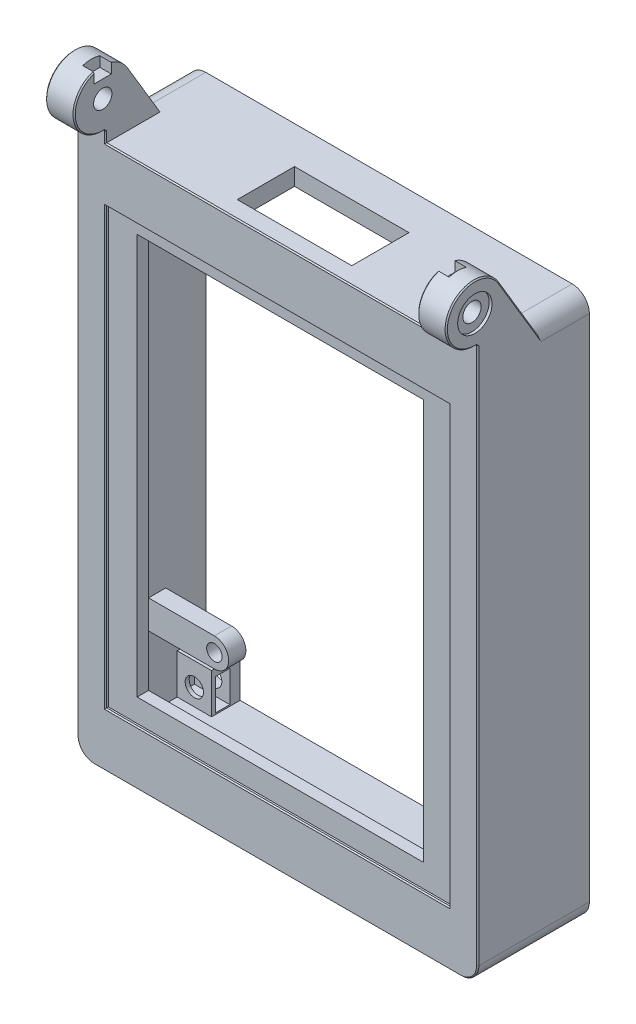
SolidWorks part; units mm, degrees
ref_plane "前视基准面" through (0, 0, 0) normal (0, 0, 1) x (1, 0, 0)
ref_plane "上视基准面" through (0, 0, 0) normal (0, 1, 0) x (1, 0, 0)
ref_plane "右视基准面" through (0, 0, 0) normal (1, 0, 0) x (0, 0, -1)
other "Configuration Table"
sketch "草图1" plane through (0, 0, 0) normal (0, 0, 1) x (1, 0, 0)
  line L1 (-35, -47.5) -> (35, -47.5)
  line L2 (-35, -47.5) -> (-35, 47.5)
  line L3 (-35, 47.5) -> (35, 47.5)
  line L4 (35, -47.5) -> (35, 47.5)
  line L5 (-35, -47.5) -> (35, 47.5) construction
  line L6 (-35, 47.5) -> (35, -47.5) construction
  point P0 (0, 0)
  dimension "D1" = 70
  dimension "D2" = 95
extrude "凸台-拉伸1" add sketch "草图1" along normal blind 20
shell "抽壳1" thickness 3
sketch "草图2" plane through (0, 0, 20) normal (0, 0, 1) x (1, 0, 0)
  line L1 (-30, -38) -> (30, -38)
  line L2 (-30, -38) -> (-30, 38)
  line L3 (-30, 38) -> (30, 38)
  line L4 (30, -38) -> (30, 38)
  line L5 (-30, -38) -> (30, 38) construction
  line L6 (-30, 38) -> (30, -38) construction
  point P0 (0, 0)
  dimension "D1" = 60
  dimension "D2" = 76
extrude "切除-拉伸1" cut sketch "草图2" against normal blind 1
sketch "草图3" plane through (0, 0, 19) normal (0, 0, 1) x (1, 0, 0)
  line L0 (30, 38) -> (-30, 38) construction
  line L5 (-25, 36) -> (25, 36)
  line L6 (-25, 36) -> (-25, -34)
  line L7 (-25, -34) -> (25, -34)
  line L8 (25, 36) -> (25, -34)
  dimension "D1" = 2
  dimension "D2" = 50
  dimension "D3" = 25
  dimension "D4" = 70
extrude "切除-拉伸2" cut sketch "草图3" against normal blind 20
ref_plane "基准面1" through (0, 0, 10) normal (0, 0, 1) x (1, 0, 0)
sketch "草图4" plane through (0, 0, 10) normal (0, 0, 1) x (1, 0, 0)
  line L13 (20.5, 33) -> (32, 33)
  line L14 (32, -44.5) -> (32, 44.5) construction
  line L15 (32, 33) -> (32, 28)
  line L16 (32, -44.5) -> (32, 44.5) construction
  line L21 (-20.5, -29.5) -> (20.5, -29.5) construction
  line L22 (-20.5, 30.5) -> (-20.5, -29.5) construction
  line L23 (20.5, 30.5) -> (-20.5, 30.5) construction
  line L24 (20.5, -29.5) -> (20.5, 30.5) construction
  line L25 (32, 28) -> (20.5, 28)
  line L26 (-20.5, 33) -> (-32, 33)
  line L29 (-32, 33) -> (-32, 28)
  line L30 (-32, 44.5) -> (-32, -44.5) construction
  line L31 (-32, 28) -> (-20.5, 28)
  line L32 (-20.5, -27) -> (-32, -27)
  line L33 (-32, 44.5) -> (-32, -44.5) construction
  line L34 (-32, -27) -> (-32, -32)
  line L35 (-32, -32) -> (-20.5, -32)
  line L36 (20.5, -27) -> (32, -27)
  line L37 (32, -27) -> (32, -32)
  line L38 (32, -32) -> (20.5, -32)
  circle A0 centre (-20.5, 30.5) radius 1.35
  circle A1 centre (20.5, 30.5) radius 1.35
  circle A2 centre (-20.5, -29.5) radius 1.35
  circle A3 centre (20.5, -29.5) radius 1.35
  arc A4 (-20.5, 28) -> (-20.5, 33) centre (-20.5, 30.5) ccw
  arc A5 (20.5, 33) -> (20.5, 28) centre (20.5, 30.5) ccw
  arc A6 (-20.5, -32) -> (-20.5, -27) centre (-20.5, -29.5) ccw
  arc A7 (20.5, -27) -> (20.5, -32) centre (20.5, -29.5) ccw
  dimension "D2" = 2.7
  dimension "D3" = 2.7
  dimension "D4" = 2.7
  dimension "D5" = 2.7
  dimension "D6" = 5
  dimension "D7" = 5
  dimension "D8" = 5
  dimension "D9" = 5
  dimension "D10" = 20.5
  dimension "D1" = 60
extrude "凸台-拉伸2" add sketch "草图4" against normal blind 3
sketch "草图5" plane through (-32, 0, 0) normal (1, 0, 0) x (0, 0, -1)
  line L0 (0, 44.5) -> (0, 37.5)
  line L1 (0, 44.5) -> (0, -44.5) construction
  line L2 (0, 37.5) -> (-5, 37.5)
  line L3 (-5, 37.5) -> (-5, 44.5)
  line L4 (-17, 44.5) -> (0, 44.5) construction
  line L5 (-5, 44.5) -> (0, 44.5)
  line L6 (4.8105, 41.5) -> (-10.1752, 41.5) construction
  line L7 (-20, 47.5) -> (0, 47.5) construction
  dimension "D1" = 5
  dimension "D2" = 6
  dimension "D3" = 7
extrude "凸台-拉伸3" add sketch "草图5" along normal blind 6
sketch "草图6" plane through (-26, 0, 0) normal (1, 0, 0) x (0, 0, -1)
  line L0 (-8.1923, 41.5) -> (5.3609, 41.5) construction
  line L1 (-20, 47.5) -> (0, 47.5) construction
  line L2 (0, 37.5) -> (0, 44.5) construction
  line L3 (-4.3, 44.25) -> (-1.8, 44.25)
  line L4 (-4.3, 44.25) -> (-4.3, 38.75)
  line L5 (-4.3, 38.75) -> (-1.8, 38.75)
  line L6 (-1.8, 44.25) -> (-1.8, 38.75)
  dimension "D1" = 6
  dimension "D2" = 2.5
  dimension "D3" = 2.75
  dimension "D4" = 2.75
  dimension "D5" = 1.8
extrude "切除-拉伸3" cut sketch "草图6" against normal blind 6.2
sketch "草图7" plane through (0, 0, 0) normal (0, 0, -1) x (-1, 0, 0)
  line L0 (-35, 47.5) -> (35, 47.5) construction
  line L1 (35, 47.5) -> (35, -47.5) construction
  circle A0 centre (29, 41.5) radius 1.6
  dimension "D3" = 3.2
  dimension "D1" = 6
  dimension "D2" = 6
extrude "切除-拉伸4" cut sketch "草图7" against normal blind 6.2
mirror "镜向1" about plane through (0, 0, 0) normal (0, 1, 0) of "凸台-拉伸3"
mirror "镜向2" about plane through (0, 0, 0) normal (1, 0, 0) of "镜向1", "凸台-拉伸3"
mirror "镜向3" about plane through (0, 0, 0) normal (0, 1, 0) of "切除-拉伸3"
mirror "镜向4" about plane through (0, 0, 0) normal (1, 0, 0) of "镜向3", "切除-拉伸3"
mirror "镜向5" about plane through (0, 0, 0) normal (0, 1, 0) of "切除-拉伸4"
mirror "镜向6" about plane through (0, 0, 0) normal (1, 0, 0) of "镜向5", "切除-拉伸4"
sketch "草图8" plane through (35, 0, 0) normal (1, 0, 0) x (0, 0, -1)
  line L0 (0, 47.5) -> (0, 49.5) construction
  line L1 (-20, 47.5) -> (0, 47.5) construction
  line L2 (0, -47.5) -> (0, 47.5) construction
  line L3 (-4.2936, 57.0623) -> (-10, 47.5) construction
  line L4 (-20, 47.5) -> (0, 47.5) construction
  line L5 (-10, 47.5) -> (-10, 58.6086) construction
  line L6 (-15.7064, 57.0623) -> (-10, 47.5)
  line L7 (-20, 47.5) -> (-20, 49.5)
  line L8 (-10, 47.5) -> (-20, 47.5)
  arc A0 (0, 49.5) -> (-4.2936, 57.0623) centre (0, 54.5) ccw construction
  arc A1 (-20, 49.5) -> (-15.7064, 57.0623) centre (-20, 54.5) cw
  dimension "D1" = 10
  dimension "D2" = 7
  dimension "D3" = 10
  dimension "D4" = 7
extrude "凸台-拉伸4" add sketch "草图8" against normal up to surface (70 mm away) up to face at (-35, 0, 10)
sketch "草图9" plane through (35, 0, 0) normal (1, 0, 0) x (0, 0, -1)
  circle A0 centre (-20, 54.5) radius 1.6
  dimension "D1" = 3.2
extrude "切除-拉伸5" cut sketch "草图9" against normal up to surface (70 mm away) up to face at (-35, 18.375, 12.0335)
sketch "草图10" plane through (0, 0, 0) normal (0, 0, -1) x (-1, 0, 0)
  line L0 (35, 59.5) -> (-35, 59.5) construction
  line L1 (-30, 59.5) -> (30, 59.5)
  line L2 (-30, 59.5) -> (-30, 47.5)
  line L3 (-30, 47.5) -> (30, 47.5)
  line L4 (30, 59.5) -> (30, 47.5)
  line L5 (35, 47.5) -> (-35, 47.5) construction
  line L6 (35, 57.0623) -> (35, 47.5) construction
  line L7 (-35, 47.5) -> (-35, 57.0623) construction
  dimension "D1" = 5
  dimension "D2" = 5
extrude "切除-拉伸6" cut sketch "草图10" against normal blind 30
sketch "草图11" plane through (-30, 0, 0) normal (1, 0, 0) x (0, 0, -1)
  line L0 (-20, 54.5) -> (-20, 62.1842) construction
  line L1 (-21.5, 64.5) -> (-18.5, 64.5)
  line L2 (-21.5, 64.5) -> (-21.5, 57.5)
  line L3 (-21.5, 57.5) -> (-18.5, 57.5)
  line L4 (-18.5, 64.5) -> (-18.5, 57.5)
  dimension "D1" = 1.5
  dimension "D2" = 1.5
  dimension "D3" = 3
  dimension "D4" = 10
extrude "切除-拉伸7" cut sketch "草图11" against normal blind 2
mirror "镜向7" about plane through (0, 0, 0) normal (1, 0, 0) of "切除-拉伸7"
sketch "草图12" plane through (35, 0, 0) normal (1, 0, 0) x (0, 0, -1)
  circle A0 centre (-20, 54.5) radius 3
  dimension "D1" = 6
extrude "切除-拉伸8" cut sketch "草图12" against normal blind 0.5
mirror "镜向8" about plane through (0, 0, 0) normal (1, 0, 0) of "切除-拉伸8"
sketch "草图13" plane through (0, 0, 20) normal (0, 0, 1) x (1, 0, 0)
  line L8 (35, 49.5) -> (30, 49.5)
  line L9 (30, 49.5) -> (30, 47.5)
  line L10 (30, 47.5) -> (-30, 47.5)
  line L11 (-30, 47.5) -> (-30, 49.5)
  line L12 (-30, 49.5) -> (-35, 49.5)
  line L13 (-35, 49.5) -> (-35, -47.5)
  line L14 (-35, -47.5) -> (35, -47.5)
  line L15 (35, -47.5) -> (35, 49.5)
  line L16 (35, 49.5) -> (30, 49.5)
  line L17 (30, 49.5) -> (30, 47.5)
  line L18 (30, 47.5) -> (-30, 47.5)
  line L19 (-30, 47.5) -> (-30, 49.5)
  line L20 (-30, 49.5) -> (-35, 49.5)
  line L21 (-35, 49.5) -> (-35, -47.5)
  line L22 (-35, -47.5) -> (35, -47.5)
  line L23 (35, -47.5) -> (35, 49.5)
  dimension "D1" = 0
extrude "切除-拉伸9" cut sketch "草图13" against normal blind 0.5
sketch "草图14" plane through (0, 47.5, 0) normal (0, 1, 0) x (1, 0, 0)
  line L1 (-10, -6.5) -> (10, -6.5)
  line L2 (-10, -6.5) -> (-10, -16.5)
  line L3 (-10, -16.5) -> (10, -16.5)
  line L4 (10, -6.5) -> (10, -16.5)
  line L5 (-35, -10) -> (-35, 0) construction
  line L6 (35, -10) -> (35, 0) construction
  line L7 (30, -19.5) -> (-30, -19.5) construction
  dimension "D1" = 25
  dimension "D2" = 25
  dimension "D3" = 3
  dimension "D4" = 10
extrude "切除-拉伸10" cut sketch "草图14" against normal blind 10
fillet "圆角1" radius 3 4 edges at (-35, -47.5, 9.75) (35, -47.5, 9.75) (35, 47.5, 5) (-35, 47.5, 5)
chamfer "倒角1" distance 0.2 angle 45 24 edges at (0, 38, 19.5) (-30, 0, 19.5) (0, -38, 19.5) (30, 0, 19.5) (-35, 50.7811, 11.9581) (35, 50.7811, 11.9581) (-30, 53.7412, 24.9421) (-35, 56.9687, 24.3481) (30, 53.7412, 24.9421) (35, 56.9687, 24.3481) (-30, 49.5, 19.75) (-35, 49.5, 19.75) (30, 49.5, 19.75) (35, 49.5, 19.75) (-32.5, 49.5, 19.5) (-30, 48.5, 19.5) (0, 47.5, 19.5) (30, 48.5, 19.5) (32.5, 49.5, 19.5) (35, 2.5, 19.5) (34.1213, -46.6213, 19.5) (0, -47.5, 19.5) (-34.1213, -46.6213, 19.5) (-35, 2.5, 19.5)
